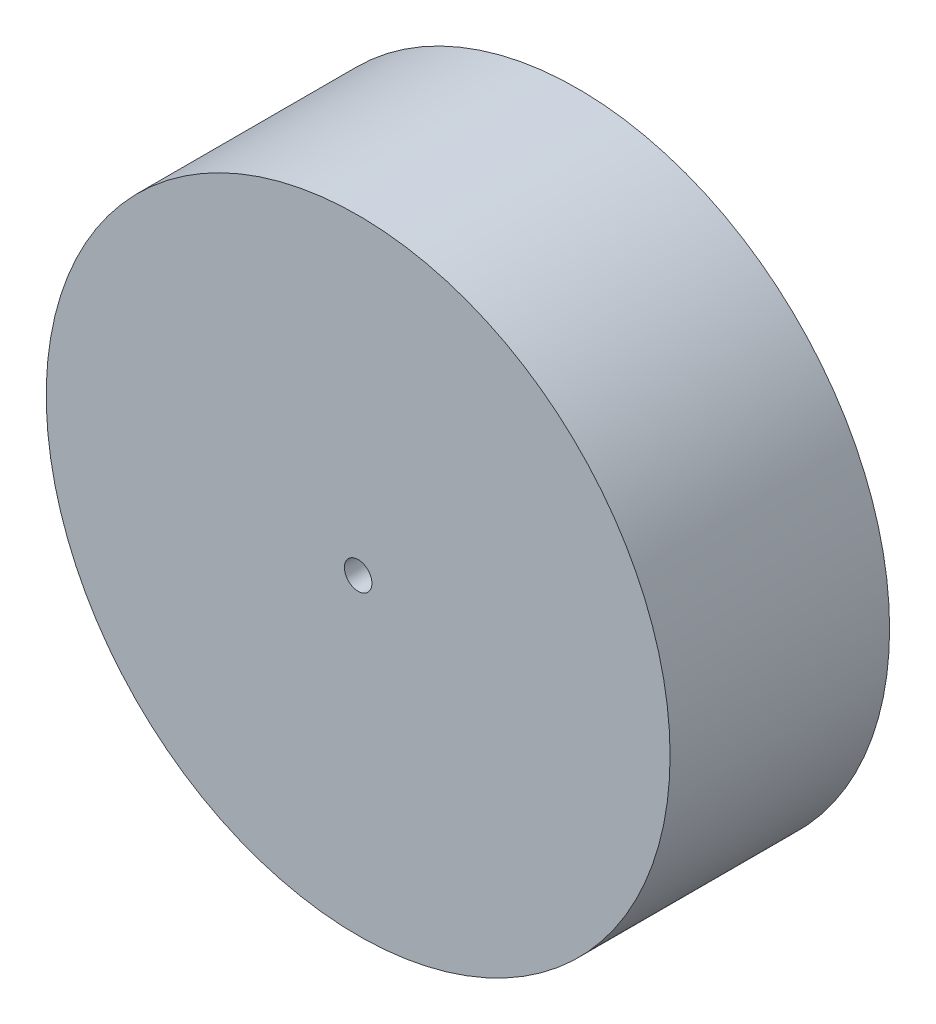
SolidWorks part; units mm, degrees
material "POLYURETHANE (11671)"
ref_plane "Front Plane" through (0, 0, 0) normal (0, 0, 1) x (1, 0, 0)
ref_plane "Top Plane" through (0, 0, 0) normal (0, 1, 0) x (1, 0, 0)
ref_plane "Right Plane" through (0, 0, 0) normal (1, 0, 0) x (0, 0, -1)
sketch "Sketch1" plane through (0, 0, 0) normal (0, 0, 1) x (1, 0, 0)
  circle A0 centre (0, 0) radius 54
  circle A1 centre (0, 0) radius 2.3813
  dimension "D1" = 108
extrude "Boss-Extrude1" add sketch "Sketch1" along normal blind 38
